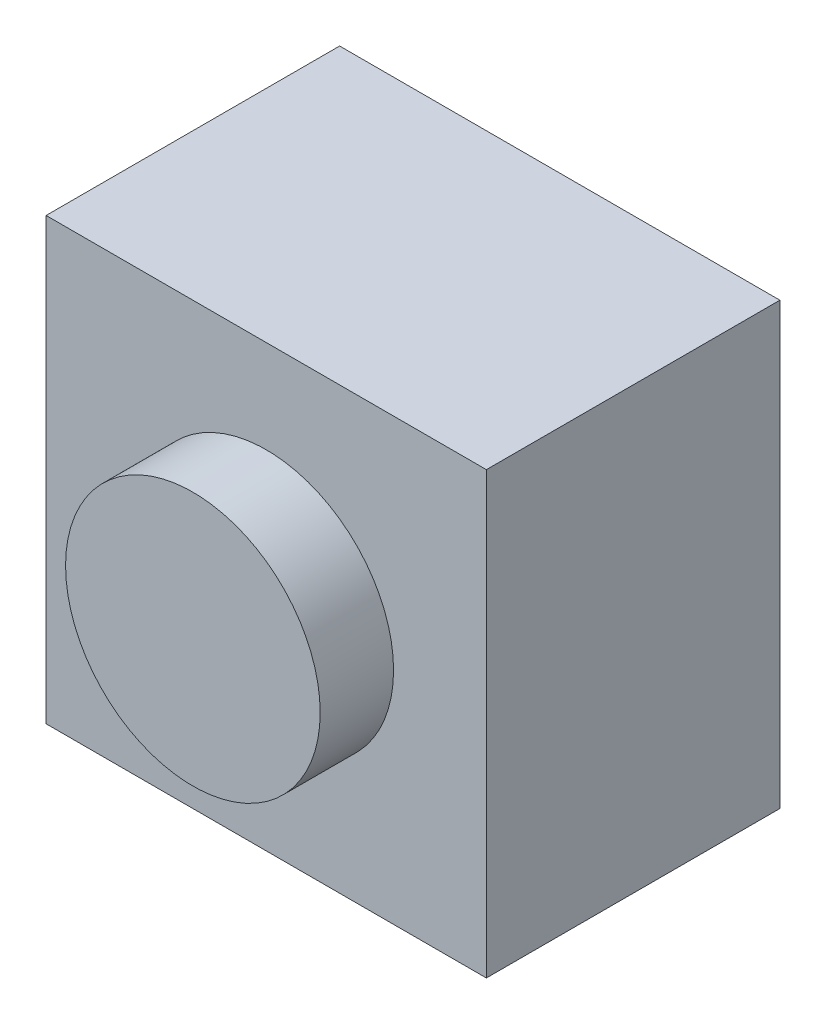
SolidWorks part; units mm, degrees
ref_plane "Front Plane" through (0, 0, 0) normal (0, 0, 1) x (1, 0, 0)
ref_plane "Top Plane" through (0, 0, 0) normal (0, 1, 0) x (1, 0, 0)
ref_plane "Right Plane" through (0, 0, 0) normal (1, 0, 0) x (0, 0, -1)
sketch "Sketch2" plane through (0, 0, 0) normal (0, 0, 1) x (1, 0, 0)
  line L1 (-3, 3) -> (3, 3)
  line L2 (-3, 3) -> (-3, -3)
  line L3 (-3, -3) -> (3, -3)
  line L4 (3, 3) -> (3, -3)
  line L5 (-3, 3) -> (3, -3) construction
  line L6 (-3, -3) -> (3, 3) construction
  point P0 (0, 0)
extrude "Boss-Extrude1" add sketch "Sketch2" along normal blind 4
sketch "Sketch3" plane through (0, 0, 4) normal (0, 0, 1) x (1, 0, 0)
  circle A0 centre (0, 0) radius 1.735
  dimension "D1" = 3.47
extrude "Boss-Extrude2" add sketch "Sketch3" along normal blind 1
